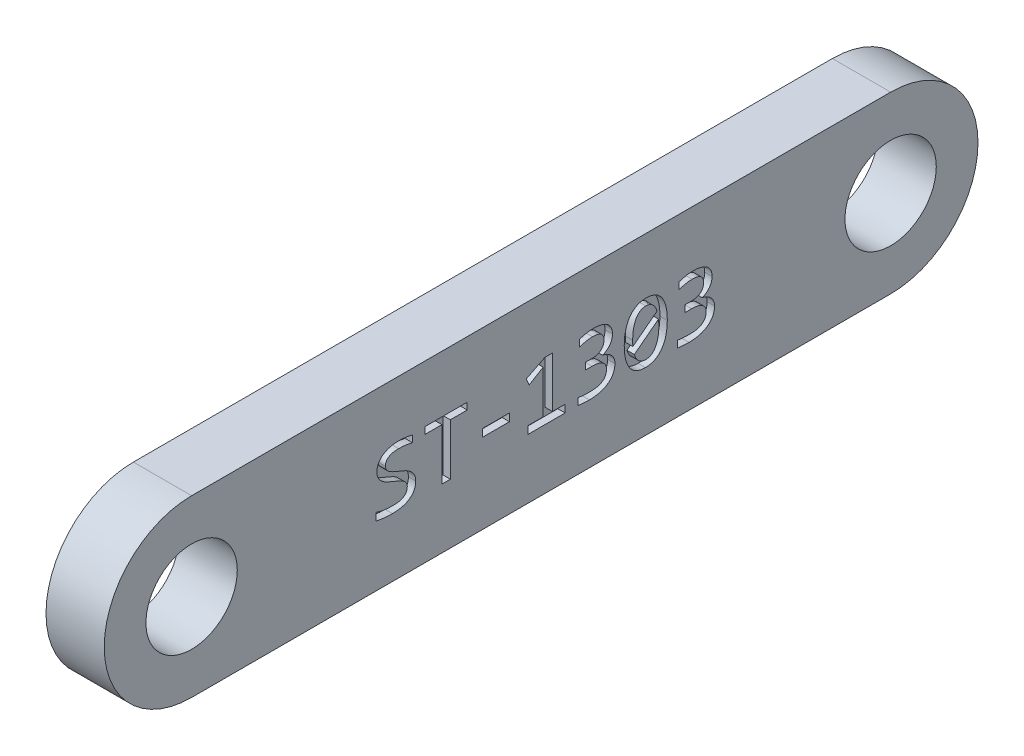
SolidWorks part; units mm, degrees
material "PET"
ref_plane "Front Plane" through (0, 0, 0) normal (0, 0, 1) x (1, 0, 0)
ref_plane "Top Plane" through (0, 0, 0) normal (0, 1, 0) x (1, 0, 0)
ref_plane "Right Plane" through (0, 0, 0) normal (1, 0, 0) x (0, 0, -1)
sketch "Sketch1" plane through (0, 0, 0) normal (1, 0, 0) x (0, 0, -1)
  line L0 (0, 0) -> (38.1, 0) construction
  line L1 (0, 4.7625) -> (38.1, 4.7625)
  line L2 (0, -4.7625) -> (38.1, -4.7625)
  arc A0 (0, 4.7625) -> (0, -4.7625) centre (0, 0) ccw
  arc A1 (38.1, -4.7625) -> (38.1, 4.7625) centre (38.1, 0) ccw
  circle A2 centre (38.1, 0) radius 2.4892
  circle A3 centre (0, 0) radius 2.4892
  point P3 (19.05, 0)
  dimension "D1" = 4.7625
  dimension "D3" = 4.9784
  dimension "D2" = 38.1
extrude "Boss-Extrude1" add sketch "Sketch1" along normal mid plane 3.175
sketch "Sketch2" plane through (0, 0, 0) normal (1, 0, 0) x (0, 0, -1)
  line L0 (-5.6204, -1.5106) -> (44.1758, -1.5106) construction
  text T0 "ST-1303" font "Consolas" height 3.175
extrude "Cut-Extrude1" cut sketch "Sketch2" against normal blind 0.4 from surface at 1.5875 starting at face at (1.5875, 0, -40.5892)
